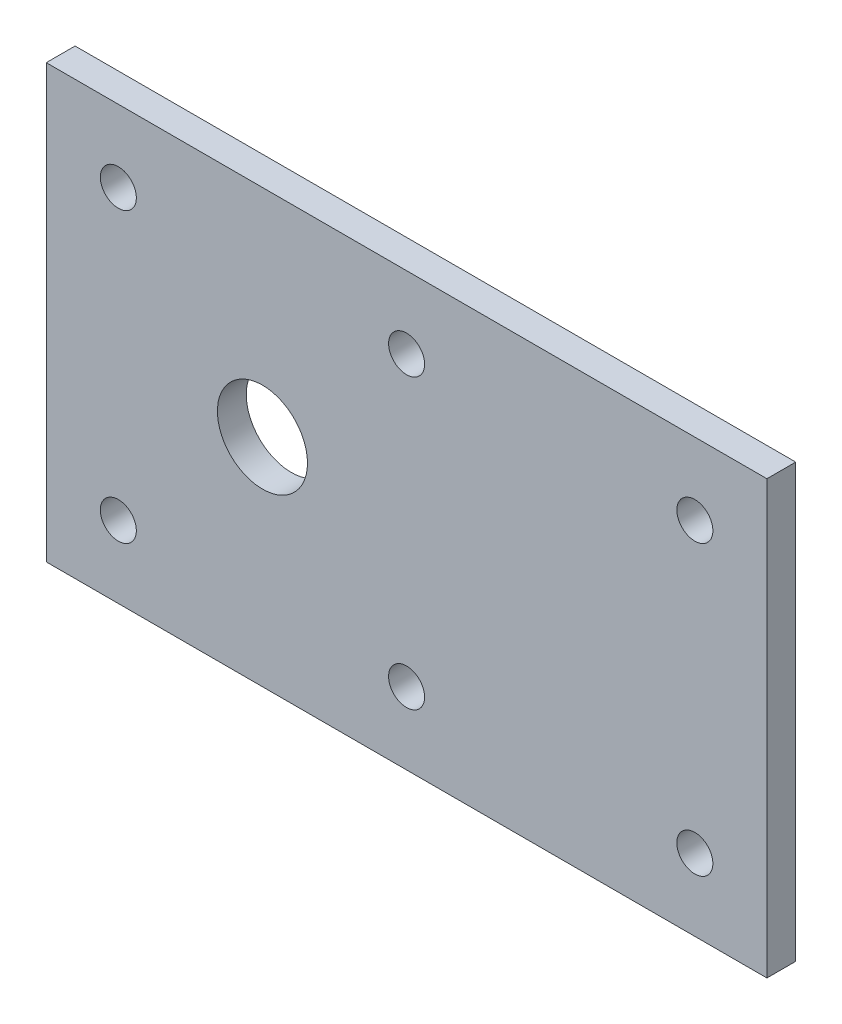
SolidWorks part; units mm, degrees
ref_plane "Front Plane" through (0, 0, 0) normal (0, 0, 1) x (1, 0, 0)
ref_plane "Top Plane" through (0, 0, 0) normal (0, 1, 0) x (1, 0, 0)
ref_plane "Right Plane" through (0, 0, 0) normal (1, 0, 0) x (0, 0, -1)
sketch "Sketch1" plane through (0, 0, 0) normal (0, 0, 1) x (1, 0, 0)
  line L0 (-60, 0) -> (140, 0) construction
  line L1 (-60, 60) -> (140, 60)
  line L2 (-60, 60) -> (-60, -60)
  line L3 (-60, -60) -> (140, -60)
  line L4 (140, 60) -> (140, -60)
  dimension "D1" = 120
  dimension "D2" = 200
  dimension "D3" = 60
extrude "Boss-Extrude2" add sketch "Sketch1" along normal blind 8
sketch "Sketch2" plane through (0, 0, 8) normal (0, 0, 1) x (1, 0, 0)
  line L0 (140, 60) -> (-60, 60) construction
  line L1 (-60, 60) -> (-60, -60) construction
  circle A0 centre (-40, 40) radius 5
  dimension "D1" = 20
  dimension "D2" = 20
extrude "Cut-Extrude1" cut sketch "Sketch2" against normal through all
pattern_linear "LPattern1" count 3 spacing 80 along (1, 0, 0) count 2 spacing 80 along (0, -1, 0) of "Cut-Extrude1"
sketch "Sketch5" plane through (0, 0, 8) normal (0, 0, 1) x (1, 0, 0)
  circle A0 centre (0, 0) radius 12.5
  point P3 (0, 0)
  dimension "D1" = 25
extrude "Cut-Extrude2" cut sketch "Sketch5" against normal through all
